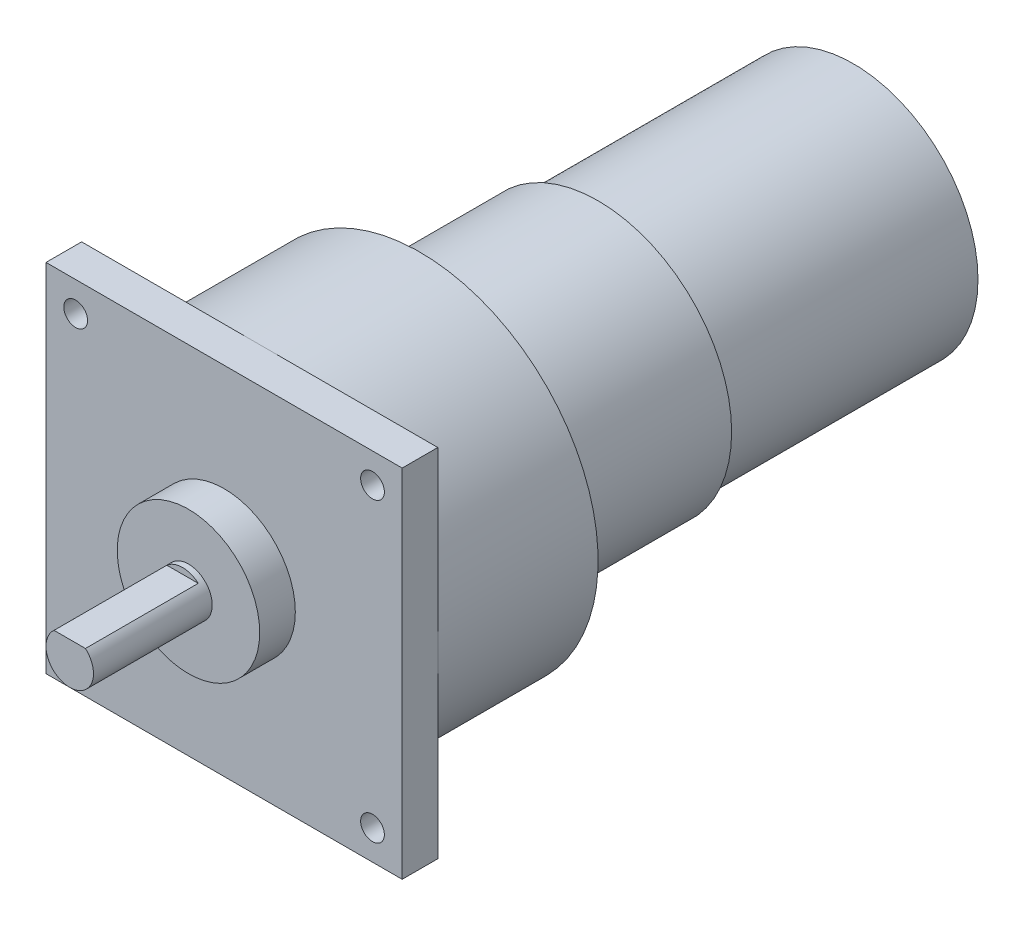
SolidWorks part; units mm, degrees
ref_plane "Front Plane" through (0, 0, 0) normal (0, 0, 1) x (1, 0, 0)
ref_plane "Top Plane" through (0, 0, 0) normal (0, 1, 0) x (1, 0, 0)
ref_plane "Right Plane" through (0, 0, 0) normal (1, 0, 0) x (0, 0, -1)
sketch "Sketch1" plane through (0, 0, 0) normal (0, 0, 1) x (1, 0, 0)
  line L1 (-30, 30) -> (30, 30)
  line L2 (-30, 30) -> (-30, -30)
  line L3 (-30, -30) -> (30, -30)
  line L4 (30, 30) -> (30, -30)
  line L5 (-30, 30) -> (30, -30) construction
  line L6 (-30, -30) -> (30, 30) construction
  circle A0 centre (-25, 25) radius 2
  circle A1 centre (25, 25) radius 2
  circle A2 centre (-25, -25) radius 2
  circle A3 centre (25, -25) radius 2
  point P0 (0, 0)
  dimension "D3" = 4
  dimension "D1" = 60
  dimension "D2" = 60
  dimension "D4" = 50
extrude "Boss-Extrude1" add sketch "Sketch1" along normal blind 6
sketch "Sketch2" plane through (0, 0, 6) normal (0, 0, 1) x (1, 0, 0)
  circle A0 centre (0, 0) radius 12
  dimension "D1" = 24
extrude "Boss-Extrude2" add sketch "Sketch2" along normal blind 6
sketch "Sketch3" plane through (0, 0, 12) normal (0, 0, 1) x (1, 0, 0)
  circle A0 centre (0, 0) radius 4
  dimension "D1" = 8
extrude "Boss-Extrude3" add sketch "Sketch3" along normal blind 20
sketch "Sketch4" plane through (0, 0, 32) normal (0, 0, 1) x (1, 0, 0)
  line L0 (-2.6458, 3) -> (2.6458, 3)
  circle A1 centre (0, 0) radius 4 construction
  arc A2 (-2.6458, 3) -> (2.6458, 3) centre (0, 0) cw
  dimension "D1" = 3
extrude "Cut-Extrude1" cut sketch "Sketch4" against normal blind 19
sketch "Sketch5" plane through (0, 0, 0) normal (0, 0, -1) x (-1, 0, 0)
  circle A0 centre (0, 0) radius 30
  dimension "D1" = 60
extrude "Boss-Extrude4" add sketch "Sketch5" along normal blind 27
sketch "Sketch6" plane through (0, 0, -27) normal (0, 0, -1) x (-1, 0, 0)
  circle A0 centre (0, 0) radius 22.5
  dimension "D1" = 45
extrude "Boss-Extrude5" add sketch "Sketch6" along normal blind 30
sketch "Sketch7" plane through (0, 0, -57) normal (0, 0, -1) x (-1, 0, 0)
  circle A0 centre (0, 0) radius 21
  dimension "D1" = 42
extrude "Boss-Extrude6" add sketch "Sketch7" along normal blind 43
